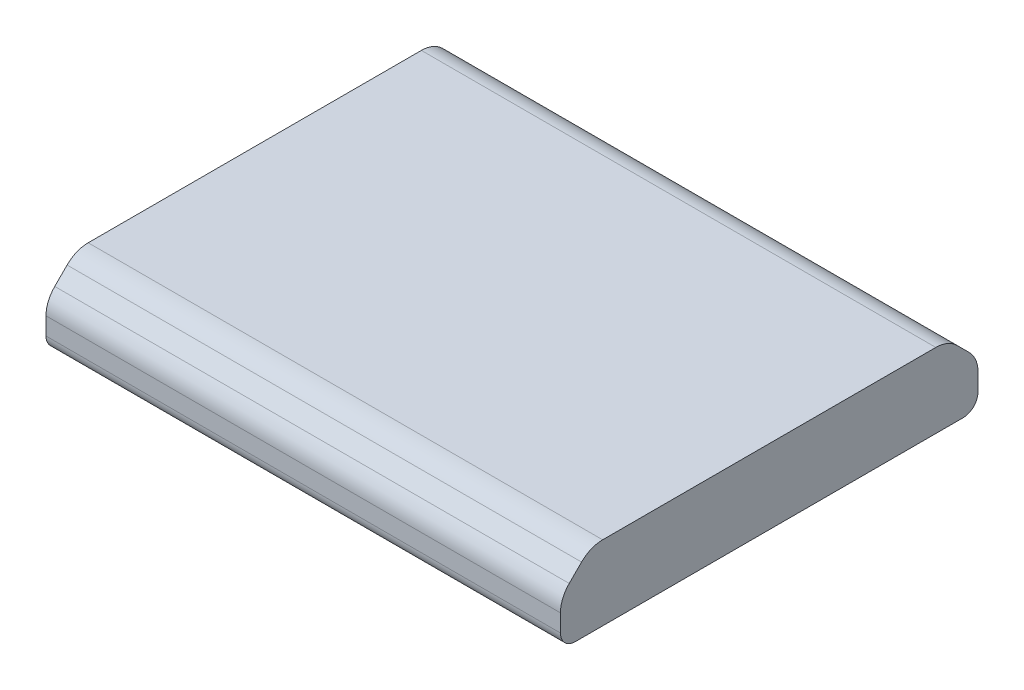
SolidWorks part; units mm, degrees
ref_plane "Front Plane" through (0, 0, 0) normal (0, 0, 1) x (1, 0, 0)
ref_plane "Top Plane" through (0, 0, 0) normal (0, 1, 0) x (1, 0, 0)
ref_plane "Right Plane" through (0, 0, 0) normal (1, 0, 0) x (0, 0, -1)
sketch "Sketch2" plane through (0, 0, 0) normal (1, 0, 0) x (0, 0, -1)
  line L0 (0, 44.4155) -> (0, -52.1401) construction
  line L1 (25.6, -4.5) -> (-25.6, -4.5) construction
  line L2 (-22.3431, -8) -> (22.3431, -8)
  line L3 (-28, -13.6569) -> (-28, -16)
  line L4 (-26, -18) -> (26, -18)
  line L5 (28, -13.6569) -> (28, -16)
  line L6 (40.7847, -4.5) -> (-39.142, -4.5) construction
  line L7 (-25.1716, -9.1716) -> (-26.8284, -10.8284)
  line L8 (25.1716, -9.1716) -> (26.8284, -10.8284)
  arc A0 (28, -16) -> (26, -18) centre (26, -16) cw
  arc A1 (-26, -18) -> (-28, -16) centre (-26, -16) cw
  arc A2 (-22.3431, -8) -> (-25.1716, -9.1716) centre (-22.3431, -12) ccw
  arc A3 (-26.8284, -10.8284) -> (-28, -13.6569) centre (-24, -13.6569) ccw
  arc A4 (25.1716, -9.1716) -> (22.3431, -8) centre (22.3431, -12) ccw
  arc A5 (28, -13.6569) -> (26.8284, -10.8284) centre (24, -13.6569) ccw
  point P1 (-28, -8)
  point P6 (28, -8)
  point P7 (17.3951, -17.9179)
  point P10 (40.7847, -4.5)
  point P12 (-39.142, -4.5)
  point P20 (28, -18)
  point P23 (-28, -18)
  point P26 (-24, -8)
  point P29 (-28, -12)
  point P32 (24, -8)
  point P35 (28, -12)
  dimension "D4" = 2
  dimension "D5" = 4
  dimension "D1" = 10
  dimension "D2" = 56
  dimension "D3" = 3.5
extrude "Boss-Extrude1" add sketch "Sketch2" along normal blind 69 from offset 35 contours L5 A5 L8 A4 L2 A2 L7 A3 L3 A1 L4 A0
